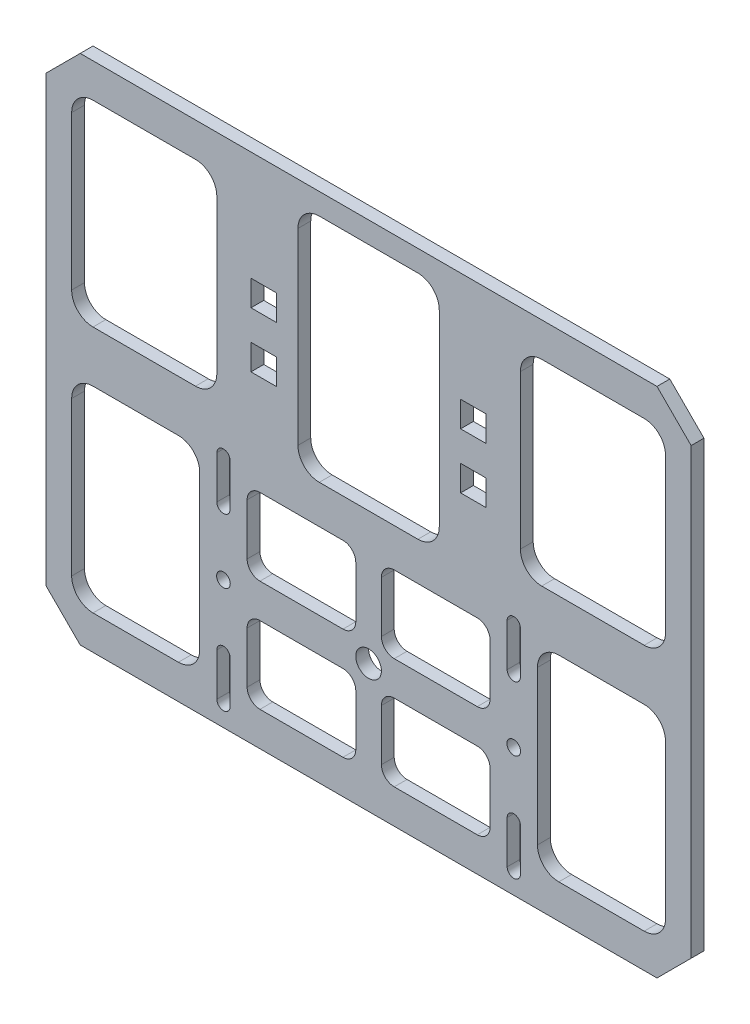
SolidWorks part; units mm, degrees
material "Thornel Mat VMA"
ref_plane "前视基准面" through (0, 0, 0) normal (0, 0, 1) x (1, 0, 0)
ref_plane "上视基准面" through (0, 0, 0) normal (0, 1, 0) x (1, 0, 0)
ref_plane "右视基准面" through (0, 0, 0) normal (1, 0, 0) x (0, 0, -1)
sketch "草图1" plane through (0, 0, 0) normal (0, 0, 1) x (1, 0, 0)
  line L0 (0, 25.3348) -> (0, -24.5642) construction
  line L1 (-32.3964, 0) -> (31.6755, 0) construction
  line L2 (35.55, -25) -> (32.45, -25)
  line L3 (-75.55, -30) -> (75.55, -30)
  line L4 (-75.55, -30) -> (-75.55, 30)
  line L5 (-75.55, 30) -> (75.55, 30)
  line L6 (75.55, -30) -> (75.55, 30)
  line L7 (-75.55, -30) -> (75.55, 30) construction
  line L8 (-75.55, 30) -> (75.55, -30) construction
  line L9 (-35.55, 25) -> (-32.45, 25)
  line L10 (-35.55, 25) -> (-35.55, 15)
  line L11 (-35.55, 15) -> (-32.45, 15)
  line L12 (-32.45, 25) -> (-32.45, 15)
  line L13 (-35.55, -15) -> (-32.45, -15)
  line L14 (-35.55, -15) -> (-35.55, -25)
  line L15 (-35.55, -25) -> (-32.45, -25)
  line L16 (-32.45, -15) -> (-32.45, -25)
  line L17 (32.45, -15) -> (32.45, -25)
  line L18 (35.55, -15) -> (32.45, -15)
  line L19 (35.55, -15) -> (35.55, -25)
  line L20 (35.55, 15) -> (32.45, 15)
  line L21 (32.45, 25) -> (32.45, 15)
  line L22 (35.55, 25) -> (32.45, 25)
  line L23 (35.55, 25) -> (35.55, 15)
  line L24 (34, -15) -> (34, 15) construction
  circle A0 centre (0, 0) radius 3
  circle A1 centre (34, 0) radius 1.6
  circle A2 centre (-34, 0) radius 1.6
  point P5 (0, 0)
  point P22 (-32.45, -20)
  point P23 (-32.45, 20)
  point P25 (-34, 15)
  dimension "D7" = 6
  dimension "D8" = 3.2
  dimension "D1" = 40
  dimension "D2" = 3.1
  dimension "D3" = 10
  dimension "D4" = 40
  dimension "D5" = 68
  dimension "D6" = 5
extrude "凸台-拉伸1" add sketch "草图1" along normal blind 3
sketch "草图2" plane through (0, 0, 3) normal (0, 0, 1) x (1, 0, 0)
  line L0 (-32.45, 25) -> (-35.55, 25) construction
  line L1 (-35.55, 15) -> (-32.45, 15) construction
  line L2 (35.55, 25) -> (32.45, 25) construction
  line L3 (32.45, 15) -> (35.55, 15) construction
  line L4 (35.55, -15) -> (32.45, -15) construction
  line L5 (32.45, -25) -> (35.55, -25) construction
  line L6 (-32.45, -15) -> (-35.55, -15) construction
  line L7 (-35.55, -25) -> (-32.45, -25) construction
  line L8 (0, 30) -> (0, -30) construction
  line L9 (75.55, 30) -> (-75.55, 30) construction
  line L10 (-75.55, -30) -> (75.55, -30) construction
  line L11 (-75.55, 0) -> (75.55, 0) construction
  line L12 (-75.55, 30) -> (-75.55, -30) construction
  line L13 (75.55, -30) -> (75.55, 30) construction
  line L14 (-32.45, -25) -> (-32.45, -15) construction
  line L15 (-28.45, 22) -> (-3, 22)
  line L16 (-28.45, 22) -> (-28.45, 4)
  line L17 (-28.45, 4) -> (-3, 4)
  line L18 (28.45, 22) -> (28.45, 4)
  line L19 (-28.45, 22) -> (28.45, 4) construction
  line L20 (-28.45, 4) -> (28.45, 22) construction
  line L21 (-28.45, -4) -> (-3, -4)
  line L22 (-28.45, -4) -> (-28.45, -22)
  line L23 (-28.45, -22) -> (-3, -22)
  line L24 (28.45, -4) -> (28.45, -22)
  line L25 (-28.45, -4) -> (28.45, -22) construction
  line L26 (-28.45, -22) -> (28.45, -4) construction
  line L27 (-3, 22) -> (-3, 4)
  line L28 (3, 22) -> (3, 4)
  line L29 (-3, -4) -> (-3, -22)
  line L30 (3, -4) -> (3, -22)
  line L31 (3, 22) -> (28.45, 22)
  line L32 (3, 4) -> (28.45, 4)
  line L33 (3, -4) -> (28.45, -4)
  line L34 (3, -22) -> (28.45, -22)
  circle A0 centre (-34, 25) radius 1.55
  circle A1 centre (-34, 15) radius 1.55
  circle A2 centre (34, 25) radius 1.55
  circle A3 centre (34, 15) radius 1.55
  circle A4 centre (34, -15) radius 1.55
  circle A5 centre (34, -25) radius 1.55
  circle A6 centre (-34, -15) radius 1.55
  circle A7 centre (-34, -25) radius 1.55
  circle A8 centre (0, 0) radius 3 construction
  point P52 (0, 13)
  point P57 (0, -13)
  dimension "D1" = 4
  dimension "D2" = 8
  dimension "D3" = 4
  dimension "D4" = 6
extrude "切除-拉伸1" cut sketch "草图2" against normal through all
fillet "圆角1" radius 3 16 edges at (-28.45, -22, 1.5) (-28.45, -4, 1.5) (-28.45, 4, 1.5) (-28.45, 22, 1.5) (3, 4, 1.5) (3, 22, 1.5) (-3, 22, 1.5) (-3, 4, 1.5) (-3, -22, 1.5) (-3, -4, 1.5) (3, -22, 1.5) (3, -4, 1.5) (28.45, -4, 1.5) (28.45, -22, 1.5) (28.45, 4, 1.5) (28.45, 22, 1.5)
sketch "草图3" plane through (0, 0, 3) normal (0, 0, 1) x (1, 0, 0)
  line L0 (75.55, -30) -> (75.55, 30) construction
  line L1 (-75.55, 90) -> (75.55, 90)
  line L2 (-75.55, 90) -> (-75.55, 30)
  line L3 (-75.55, 30) -> (75.55, 30)
  line L4 (75.55, 90) -> (75.55, 30)
  line L5 (0, 0) -> (0, 90) construction
  line L6 (27.55, 45.4) -> (21.55, 45.4)
  line L7 (-27.55, 64.4) -> (-21.55, 64.4)
  line L8 (-27.55, 64.4) -> (-27.55, 58.4)
  line L9 (-27.55, 58.4) -> (-21.55, 58.4)
  line L10 (-21.55, 64.4) -> (-21.55, 58.4)
  line L11 (-27.55, 51.4) -> (-21.55, 51.4)
  line L12 (-27.55, 51.4) -> (-27.55, 45.4)
  line L13 (-27.55, 45.4) -> (-21.55, 45.4)
  line L14 (-21.55, 51.4) -> (-21.55, 45.4)
  line L19 (21.55, 51.4) -> (21.55, 45.4)
  line L20 (27.55, 51.4) -> (21.55, 51.4)
  line L21 (27.55, 51.4) -> (27.55, 45.4)
  line L22 (27.55, 58.4) -> (21.55, 58.4)
  line L23 (21.55, 64.4) -> (21.55, 58.4)
  line L24 (27.55, 64.4) -> (21.55, 64.4)
  line L25 (27.55, 64.4) -> (27.55, 58.4)
  line L27 (-16.55, 85) -> (16.55, 85)
  line L28 (-16.55, 85) -> (-16.55, 31)
  line L29 (-16.55, 31) -> (16.55, 31)
  line L30 (16.55, 85) -> (16.55, 31)
  dimension "D1" = 60
  dimension "D2" = 48
  dimension "D3" = 54
  dimension "D4" = 6
  dimension "D5" = 13
  dimension "D6" = 15.4
  dimension "D7" = 5
  dimension "D8" = 1
  dimension "D9" = 5
  dimension "D10" = 43.1
  dimension "D11" = 55.1
extrude "凸台-拉伸2" add sketch "草图3" against normal up to surface (3 mm away) up to face at (34, -20, 0)
sketch "草图4" plane through (0, 0, 3) normal (0, 0, 1) x (1, 0, 0)
  line L1 (-69.55, 82) -> (-35.55, 82)
  line L2 (-69.55, 82) -> (-69.55, 36)
  line L3 (-69.55, 36) -> (-35.55, 36)
  line L4 (-35.55, 82) -> (-35.55, 36)
  line L5 (-69.55, 24) -> (-39.55, 24)
  line L6 (-69.55, 24) -> (-69.55, -22)
  line L7 (-69.55, -22) -> (-39.55, -22)
  line L8 (-39.55, 24) -> (-39.55, -22)
  line L17 (0, 90) -> (0, 0) construction
  line L18 (75.55, 90) -> (-75.55, 90) construction
  line L19 (-75.55, 30) -> (75.55, 30) construction
  line L20 (-75.55, 90) -> (-75.55, -30) construction
  line L21 (75.55, -30) -> (75.55, 90) construction
  line L22 (-35.55, 25) -> (-35.55, 15) construction
  line L23 (-27.55, 64.4) -> (-27.55, 58.4) construction
  line L24 (69.55, -22) -> (39.55, -22)
  line L25 (39.55, 24) -> (39.55, -22)
  line L26 (69.55, 24) -> (39.55, 24)
  line L27 (69.55, 24) -> (69.55, -22)
  line L28 (69.55, 36) -> (35.55, 36)
  line L29 (35.55, 82) -> (35.55, 36)
  line L30 (69.55, 82) -> (35.55, 82)
  line L31 (69.55, 82) -> (69.55, 36)
  dimension "D1" = 6
  dimension "D2" = 4
  dimension "D3" = 8
  dimension "D4" = 6
  dimension "D5" = 6
  dimension "D6" = 8
extrude "切除-拉伸2" cut sketch "草图4" against normal through all
fillet "圆角2" radius 5 20 edges at (69.55, 24, 1.5) (69.55, -22, 1.5) (39.55, -22, 1.5) (39.55, 24, 1.5) (69.55, 36, 1.5) (69.55, 82, 1.5) (35.55, 82, 1.5) (35.55, 36, 1.5) (16.55, 31, 1.5) (16.55, 85, 1.5) (-16.55, 85, 1.5) (-16.55, 31, 1.5) (-39.55, -22, 1.5) (-69.55, -22, 1.5) (-39.55, 24, 1.5) (-69.55, 24, 1.5) (-69.55, 36, 1.5) (-69.55, 82, 1.5) (-35.55, 82, 1.5) (-35.55, 36, 1.5)
chamfer "倒角1" distance 8 angle 45 4 edges at (-75.55, -30, 1.5) (75.55, -30, 1.5) (75.55, 90, 1.5) (-75.55, 90, 1.5)
